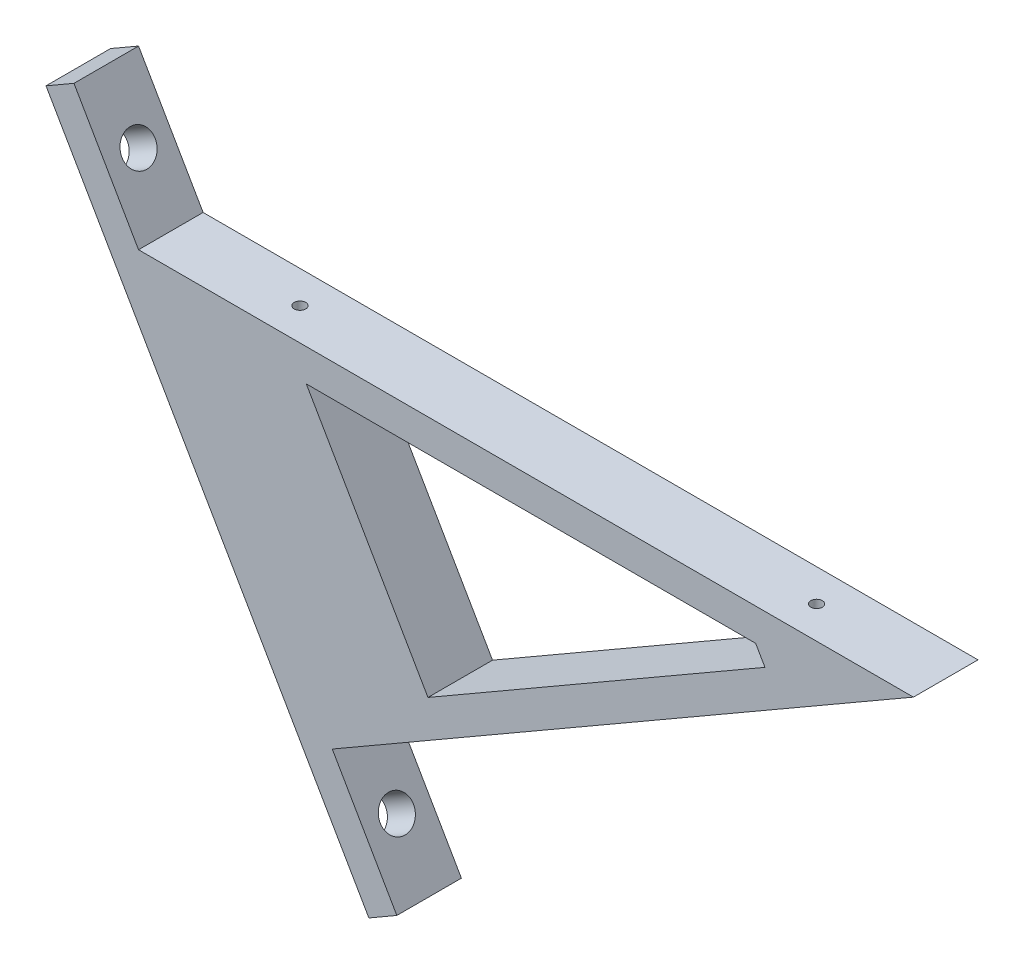
SolidWorks part; units mm, degrees
ref_plane "Front Plane" through (0, 0, 0) normal (0, 0, 1) x (1, 0, 0)
ref_plane "Top Plane" through (0, 0, 0) normal (0, 1, 0) x (1, 0, 0)
ref_plane "Right Plane" through (0, 0, 0) normal (1, 0, 0) x (0, 0, -1)
sketch "Sketch1" plane through (0, 0, 0) normal (0, 0, 1) x (1, 0, 0)
  line L0 (0, 0) -> (-114.3, -65.9911)
  line L1 (-114.3, -65.9911) -> (-152.4, 0)
  line L2 (-152.4, 0) -> (0, 0)
  line L4 (-152.4, 0) -> (-157.8993, -3.175)
  line L5 (-157.8993, -3.175) -> (-119.7993, -69.1661)
  line L6 (-119.7993, -69.1661) -> (-114.3, -65.9911)
  line L7 (-114.3, -65.9911) -> (-101.6, -87.9882)
  line L8 (-101.6, -87.9882) -> (-107.0993, -91.1632)
  line L9 (-107.0993, -91.1632) -> (-119.7993, -69.1661)
  line L10 (-119.4044, -6.35) -> (-31.0309, -6.35)
  line L11 (-29.1978, -9.525) -> (-95.478, -47.7919)
  line L12 (-95.478, -47.7919) -> (-119.4044, -6.35)
  line L13 (-152.4, 0) -> (-165.1, 21.997)
  line L14 (-165.1, 21.997) -> (-170.5993, 18.822)
  line L15 (-170.5993, 18.822) -> (-157.8993, -3.175)
  line L16 (-31.0309, -6.35) -> (-29.1978, -9.525)
  dimension "D1" = 60
  dimension "D2" = 90
  dimension "D3" = 6.35
  dimension "D4" = 25.4
  dimension "D5" = 6.35
  dimension "D6" = 25.4
  dimension "D7" = 6.35
  dimension "D8" = 25.4
  dimension "D9" = 76.5337
extrude "Boss-Extrude1" add sketch "Sketch1" along normal blind 12.7 contours L2 L1 L0 L10 L16 L11 L12 | L14 L15 L4 L13 | L5 L6 L1 L4 | L9 L8 L7 L6
sketch "Sketch2" plane through (0, 0, 0) normal (0, 1, 0) x (1, 0, 0)
  line L0 (-152.4, -12.7) -> (0, -12.7) construction
  line L1 (0, -12.7) -> (0, 0) construction
  line L2 (-152.4, -12.7) -> (-152.4, 0) construction
  circle A0 centre (-127, -6.35) radius 1.1303
  circle A1 centre (-25.4, -6.35) radius 1.1303
  point P4 (0, 0)
  point P9 (-130.7091, -6.35)
  dimension "D4" = 2.2606
  dimension "D1" = 6.35
  dimension "D2" = 25.4
  dimension "D3" = 25.4
extrude "Cut-Extrude1" cut sketch "Sketch2" against normal blind 10
sketch "Sketch3" plane through (-114.3, -65.9911, 0) normal (0.866, 0.5, 0) x (0, 0, -1)
  line L0 (0, 76.2) -> (0, 101.6) construction
  line L1 (-12.7, 101.6) -> (0, 101.6) construction
  circle A0 centre (-6.35, 88.9) radius 3.2639
  circle A1 centre (-6.35, -12.7) radius 3.2639
  point P4 (0, 0)
  point P5 (-5.7122, 91.1464)
  dimension "D2" = 6.5278
  dimension "D1" = 6.35
  dimension "D3" = 101.6
  dimension "D4" = 12.7
extrude "Cut-Extrude2" cut sketch "Sketch3" against normal blind 10
equation "\"D3@Sketch2\"=\"D2@Sketch2\""
